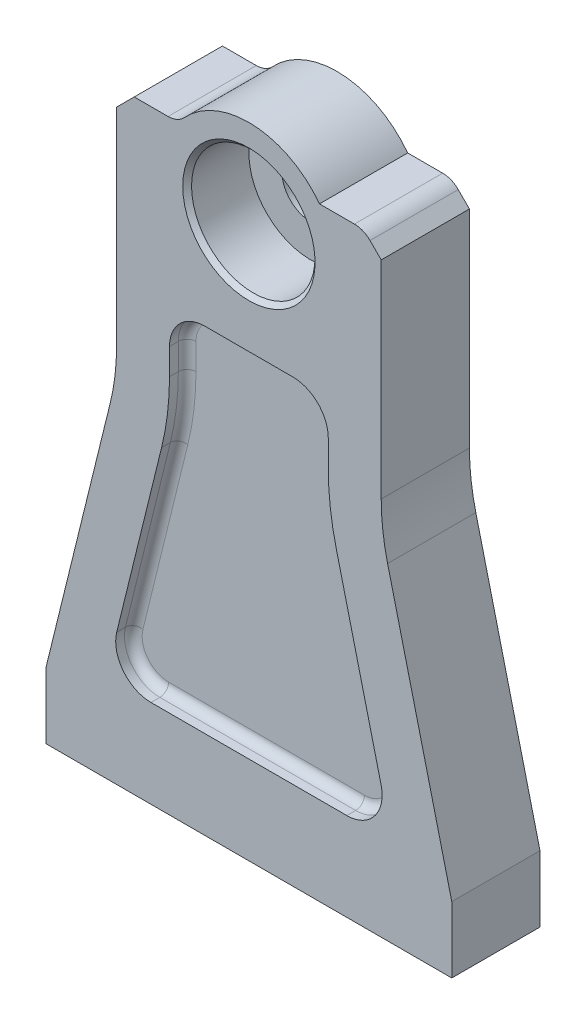
SolidWorks part; units mm, degrees
ref_plane "Front Plane" through (0, 0, 0) normal (0, 0, 1) x (1, 0, 0)
ref_plane "Top Plane" through (0, 0, 0) normal (0, 1, 0) x (1, 0, 0)
ref_plane "Right Plane" through (0, 0, 0) normal (1, 0, 0) x (0, 0, -1)
sketch "Sketch1" plane through (0, 0, 0) normal (0, 0, 1) x (1, 0, 0)
  line L0 (-46, 0) -> (46, 0)
  line L1 (46, 0) -> (46, 15)
  line L2 (46, 15) -> (31.4493, 74.1124)
  line L3 (30, 86.0633) -> (30, 137)
  line L4 (30, 137) -> (16, 137)
  line L5 (0, 125) -> (0, 0) construction
  line L6 (-30, 137) -> (-16, 137)
  line L7 (-30, 86.0633) -> (-30, 137)
  line L8 (-46, 15) -> (-31.4493, 74.1124)
  line L9 (-46, 0) -> (-46, 15)
  circle A0 centre (0, 125) radius 6.5
  arc A1 (16, 137) -> (-16, 137) centre (0, 125) ccw
  arc A2 (31.4493, 74.1124) -> (30, 86.0633) centre (80, 86.0633) cw
  arc A3 (-30, 86.0633) -> (-31.4493, 74.1124) centre (-80, 86.0633) cw
  point P9 (46, 7.5)
  point P16 (-46, 7.5)
  point P18 (30, 80)
  point P21 (-30, 80)
  dimension "D2" = 13
  dimension "D3" = 40
  dimension "D9" = 50
  dimension "D1" = 125
  dimension "D4" = 46
  dimension "D5" = 15
  dimension "D6" = 65
  dimension "D7" = 12
  dimension "D8" = 30
extrude "Boss-Extrude1" add sketch "Sketch1" along normal mid plane 20
sketch "Sketch2" plane through (0, 0, 10) normal (0, 0, 1) x (1, 0, 0)
  circle A0 centre (0, 125) radius 14
  dimension "D1" = 28
extrude "Cut-Extrude1" cut sketch "Sketch2" against normal blind 14
chamfer "Chamfer1" distance 1 angle 45 1 edges at (14, 125, 10)
chamfer "Chamfer2" distance 4 angle 45 2 edges at (-30, 137, 0) (30, 137, 0)
fillet "Fillet1" radius 5 2 edges at (-16, 137, 0) (26, 137, 0)
sketch "Sketch3" plane through (0, 0, 10) normal (0, 0, 1) x (1, 0, 0)
  line L47 (-18, 133) -> (-18, 86.0633)
  line L48 (-19.7971, 71.2442) -> (-34.3478, 12.1318)
  line L49 (-18, 92) -> (-18, 86.0633)
  line L50 (-19.7971, 71.2442) -> (-29.9711, 29.9122)
  line L52 (-10, 100) -> (10, 100)
  line L53 (34.3478, 12.1318) -> (19.7971, 71.2442)
  line L54 (18, 86.0633) -> (18, 133)
  line L55 (29.9711, 29.9122) -> (19.7971, 71.2442)
  line L56 (18, 86.0633) -> (18, 92)
  line L57 (-46, 20) -> (46, 20)
  line L58 (-22.203, 20) -> (22.203, 20)
  line L59 (-46, 0) -> (46, 0) construction
  arc A22 (-19.7971, 71.2442) -> (-18, 86.0633) centre (-80, 86.0633) ccw
  arc A23 (-19.7971, 71.2442) -> (-18, 86.0633) centre (-80, 86.0633) ccw
  arc A24 (18, 92) -> (10, 100) centre (10, 92) ccw
  arc A25 (18, 86.0633) -> (19.7971, 71.2442) centre (80, 86.0633) ccw
  arc A26 (18, 86.0633) -> (19.7971, 71.2442) centre (80, 86.0633) ccw
  arc A27 (-18, 92) -> (-10, 100) centre (-10, 92) cw
  arc A28 (29.9711, 29.9122) -> (22.203, 20) centre (22.203, 28) cw
  arc A29 (-29.9711, 29.9122) -> (-22.203, 20) centre (-22.203, 28) ccw
  dimension "D5" = 8
  dimension "D6" = 8
  dimension "D4" = 100
  dimension "D1" = 12
  dimension "D2" = 12
  dimension "D3" = 20
extrude "Cut-Extrude2" cut sketch "Sketch3" against normal blind 4
fillet "Fillet2" radius 2 12 edges at (18, 89.0317, 6) (18.4509, 78.5995, 6) (24.8841, 50.5782, 6) (28.4997, 23.0653, 6) (0, 20, 6) (-28.4997, 23.0653, 6) (-24.8841, 50.5782, 6) (-18.4509, 78.5995, 6) (-18, 89.0317, 6) (-15.6569, 97.6569, 6) (0, 100, 6) (15.6569, 97.6569, 6)
mirror "Mirror1" about plane through (0, 0, 0) normal (0, 0, 1) of "Fillet2", "Cut-Extrude2"
hole_wizard "M10x1.25 Tapped Hole1" positions "Sketch13" profile "Sketch14" tap size "M10x1.25" standard "ISO"
sketch "Sketch13" plane through (0, 0, 0) normal (0, -1, 0) x (-1, 0, 0)
  line L0 (-46, -10) -> (-46, 10) construction
  line L1 (46, -10) -> (-46, -10) construction
  point P0 (-30, 0)
  point P2 (30, 0)
  dimension "D1" = 60
  dimension "D2" = 16
  dimension "D3" = 10
sketch "Sketch14" plane through (30, 0, 0) normal (1, 0, 0) x (0, 0, -1)
  line L0 (0, 0) -> (0, 22.6438)
  line L1 (0, 22.6438) -> (4.4, 20)
  line L2 (4.4, 20) -> (4.4, 0.6)
  line L3 (4.4, 0.6) -> (5, 0)
  line L5 (5, 0) -> (0, 0)
  line L6 (-4.4, 0.6) -> (-5, 0) construction
  line L10 (0, 22.6438) -> (-4.4, 20) construction
  line L11 (0, -6.35) -> (0, 107.95) construction
  dimension "Tap Drill Dia." = 8.8
  dimension "Tap Drill Depth" = 20
  dimension "Near C'Sink Dia." = 10
  dimension "Near C'Sink Angle" = 90
  dimension "Drill Angle" = 118
cosmetic thread "Hole Thread1" parameters "D1"=20, "D2"=10
cosmetic thread "Hole Thread2" parameters "D1"=20, "D2"=10
